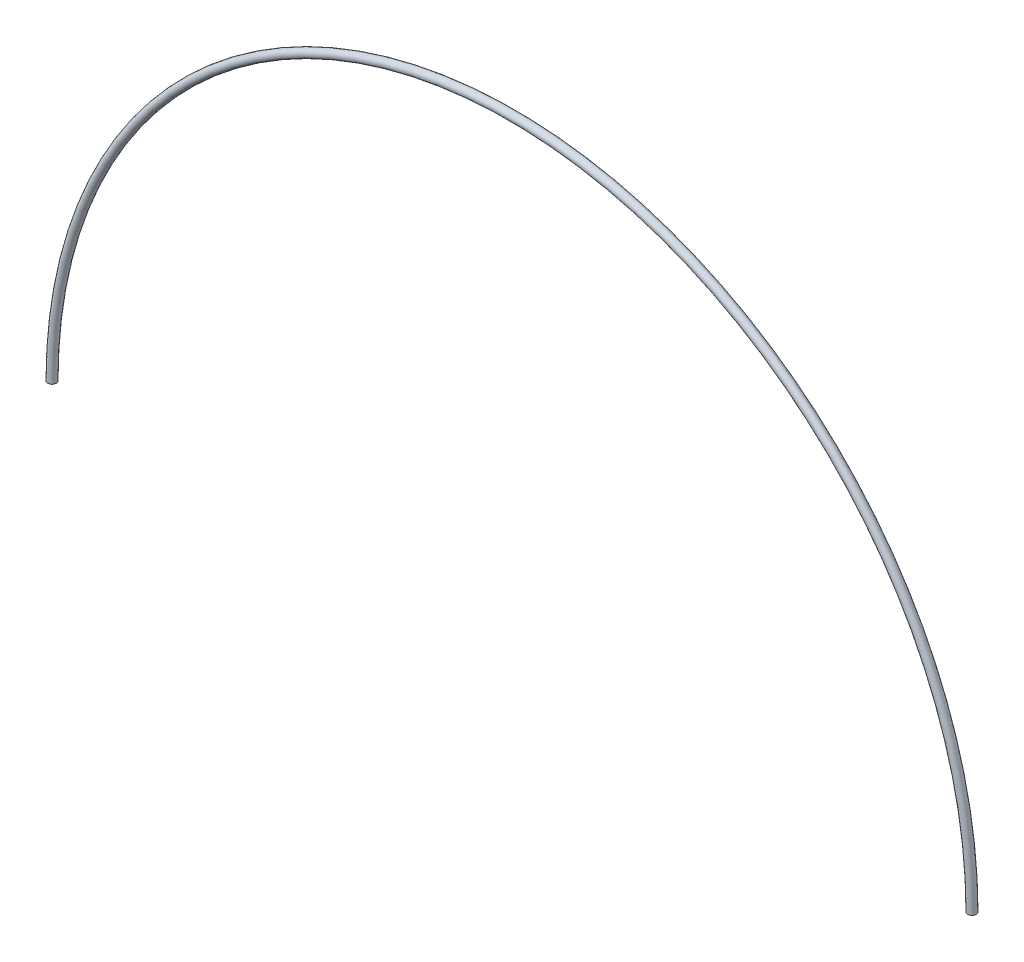
SolidWorks part; units mm, degrees
material "Galvanized Steel"
ref_plane "Front Plane" through (0, 0, 0) normal (0, 0, 1) x (1, 0, 0)
ref_plane "Top Plane" through (0, 0, 0) normal (0, 1, 0) x (1, 0, 0)
ref_plane "Right Plane" through (0, 0, 0) normal (1, 0, 0) x (0, 0, -1)
sketch "Sketch7" plane through (0, 0, 0) normal (0, 0, 1) x (1, 0, 0)
  arc A0 (0, 0) -> (3200.4, 0) centre (1600.2, 0) cw
  dimension "D1" = 3200.4
sketch "Sketch11" plane through (0, 0, 0) normal (0, 1, 0) x (1, 0, 0)
  circle A0 centre (0, 0) radius 13.3223
  circle A1 centre (0, 0) radius 14.7701
  dimension "D1" = 29.5402
  dimension "D2" = 26.6446
sweep "Sweep1" add profiles "Sketch11" path "Sketch7"
